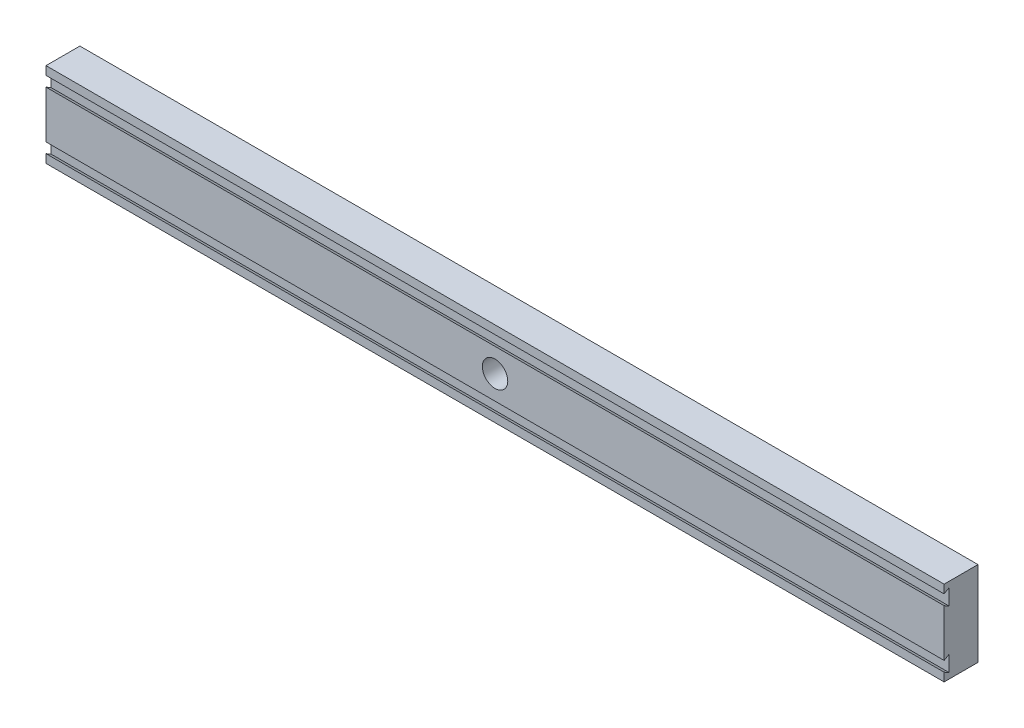
SolidWorks part; units mm, degrees
ref_plane "Front Plane" through (0, 0, 0) normal (0, 0, 1) x (1, 0, 0)
ref_plane "Top Plane" through (0, 0, 0) normal (0, 1, 0) x (1, 0, 0)
ref_plane "Right Plane" through (0, 0, 0) normal (1, 0, 0) x (0, 0, -1)
sketch "Sketch2" plane through (0, 0, 0) normal (1, 0, 0) x (0, 0, -1)
  line L0 (-10, 0) -> (10, 0) construction
  line L1 (-10, -25) -> (10, -25)
  line L2 (-10, -25) -> (-10, 25)
  line L3 (-10, 25) -> (10, 25)
  line L4 (10, -25) -> (10, 25)
  line L5 (-10, -25) -> (10, 25) construction
  line L6 (-10, 25) -> (10, -25) construction
  line L7 (-10, 14) -> (-10, 20)
  line L8 (-10, 20) -> (-7, 21.7321)
  line L9 (-7, 21.7321) -> (-7, 12.2679)
  line L10 (-7, 12.2679) -> (-10, 14)
  line L11 (-7, -12.2679) -> (-10, -14)
  line L12 (-7, -21.7321) -> (-7, -12.2679)
  line L13 (-10, -20) -> (-7, -21.7321)
  line L14 (-10, -20) -> (-10, -14)
  point P0 (0, 0)
  dimension "D1" = 50
  dimension "D2" = 20
  dimension "D3" = 6
  dimension "D4" = 60
  dimension "D5" = 60
  dimension "D6" = 5
  dimension "D7" = 3
extrude "Boss-Extrude1" add sketch "Sketch2" along normal mid plane 530 contours L13 L2 L1 L4 L3 L8 L9 L10 L11 L12
sketch "Sketch3" plane through (0, 0, 0) normal (0, 0, 1) x (1, 0, 0)
  circle A0 centre (0, 0) radius 7.5
  dimension "D1" = 15
extrude "Cut-Extrude2" cut sketch "Sketch3" against normal through all both and the other way through all
scale "Scale1" scale about centroid uniform scaling yes scale factor 0.25
